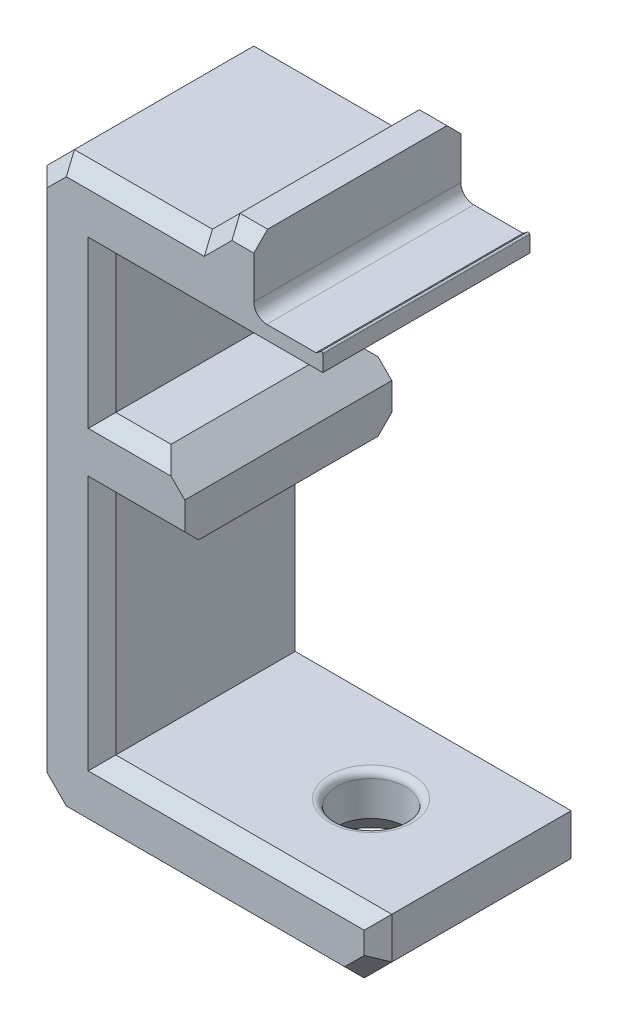
SolidWorks part; units mm, degrees
ref_plane "Plano frontal" through (0, 0, 0) normal (0, 0, 1) x (1, 0, 0)
ref_plane "Plano superior" through (0, 0, 0) normal (0, 1, 0) x (1, 0, 0)
ref_plane "Plano direito" through (0, 0, 0) normal (1, 0, 0) x (0, 0, -1)
sketch "Esboço1" plane through (0, 0, 0) normal (0, 0, 1) x (1, 0, 0)
  line L0 (11, 14.25) -> (-5, 14.25)
  line L1 (1, -0.75) -> (-5, -0.75)
  line L2 (-5, 14.25) -> (-5, 4.25)
  line L3 (-5, -17.25) -> (15, -17.25)
  line L4 (15, -17.25) -> (15, -22.25)
  line L5 (15, -22.25) -> (-10, -22.25)
  line L6 (-10, -22.25) -> (-10, 19.25)
  line L7 (1, 4.25) -> (1, -0.75)
  line L8 (1, 4.25) -> (-5, 4.25)
  line L9 (-5, -0.75) -> (-5, -17.25)
  line L10 (11, 14.25) -> (11, 16.25)
  line L11 (10.5044, 16.25) -> (6, 16.25)
  line L12 (6, 16.25) -> (6, 19.25)
  line L13 (6, 19.25) -> (-10, 19.25)
  line L14 (11, 16.25) -> (11, 16.4263)
  arc A0 (11, 16.4263) -> (10.8262, 16.4939) centre (10.9, 16.4263) ccw
  arc A1 (10.5044, 16.25) -> (10.8262, 16.4939) centre (10, 17.25) ccw
  dimension "D12" = 0.1
  dimension "D1" = 5
  dimension "D2" = 20
  dimension "D3" = 16.5
  dimension "D4" = 6
  dimension "D5" = 5
  dimension "D6" = 5
  dimension "D7" = 2
  dimension "D8" = 5
  dimension "D9" = 10
  dimension "D10" = 16
  dimension "D11" = 5
  dimension "D13" = 0.1763
  dimension "D14" = 0.4956
extrude "Ressalto-extrusão1" add sketch "Esboço1" along normal blind 15
sketch "Esboço3" plane through (0, -22.25, 0) normal (0, -1, 0) x (1, 0, 0)
  line L0 (15, 7.5) -> (7, 7.5) construction
  line L1 (15, 15) -> (15, 0) construction
  circle A0 centre (7, 7.5) radius 2.5
  dimension "D1" = 5
  dimension "D2" = 8
extrude "Corte-extrusão1" cut sketch "Esboço3" against normal blind 15
chamfer "Chanfro1" distance 2 angle 45 1 edges at (7, -22.25, 5)
fillet "Filete1" radius 0.5 1 edges at (7, -17.25, 5)
fillet "Filete2" radius 0.94 1 edges at (6, 16.25, 7.5)
sketch "Esboço5" plane through (0, 0, 15) normal (0, 0, 1) x (1, 0, 0)
  line L0 (6, 19.25) -> (6, 21.25)
  line L1 (6, 21.25) -> (4, 21.25)
  line L2 (4, 21.25) -> (2, 19.25)
  line L3 (6, 19.25) -> (-10, 19.25) construction
  line L4 (2, 19.25) -> (6, 19.25)
  dimension "D1" = 135
  dimension "D2" = 2
  dimension "D3" = 2
extrude "Ressalto-extrusão3" add sketch "Esboço5" against normal up to surface (15 mm away) up to face at (3.1829, 4.5565, 0)
chamfer "Chanfro5" distance 2 angle 45 4 edges at (15, -22.25, 7.5) (-10, -22.25, 7.5) (-10, 19.25, 7.5) (1, 4.25, 7.5)
chamfer "Chanfro4" distance 1 angle 45 33 edges at (-5, -9, 0) (-5, -9, 15) (-5, 9.25, 0) (-5, 9.25, 15) (3, 14.25, 0) (3, 14.25, 15) (11, 14.25, 7.5) (-3, 4.25, 0) (-3, 4.25, 15) (5, -17.25, 0) (15, -17.25, 7.5) (5, -17.25, 15) (-2, -0.75, 0) (1, -0.75, 7.5) (-2, -0.75, 15) (5, 21.25, 0) (5, 21.25, 15) (3, 20.25, 0) (3, 20.25, 15) (-3, 19.25, 0) (-9, 18.25, 0) (-10, -1.5, 0) (-9, -21.25, 0) (2.5, -22.25, 0) (14, -21.25, 0) (15, -18.75, 0) (-3, 19.25, 15) (-9, 18.25, 15) (-10, -1.5, 15) (-9, -21.25, 15) (2.5, -22.25, 15) (14, -21.25, 15) (15, -18.75, 15)
